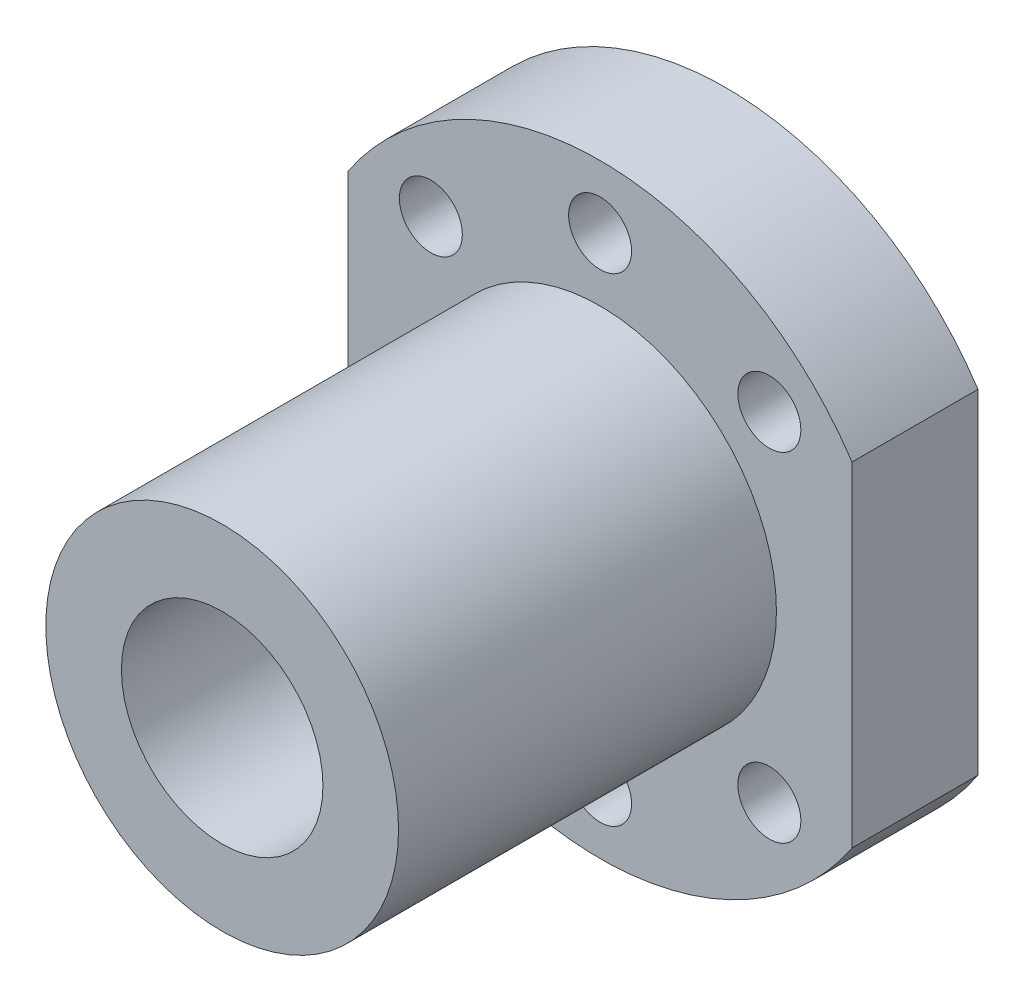
SolidWorks part; units mm, degrees
ref_plane "前视基准面" through (0, 0, 0) normal (0, 0, 1) x (1, 0, 0)
ref_plane "上视基准面" through (0, 0, 0) normal (0, 1, 0) x (1, 0, 0)
ref_plane "右视基准面" through (0, 0, 0) normal (1, 0, 0) x (0, 0, -1)
sketch "草图1" plane through (0, 0, 0) normal (0, 0, 1) x (1, 0, 0)
  line L0 (0, 24) -> (0, -24) construction
  line L1 (20, 13.2665) -> (20, -13.2665)
  line L2 (-20, -13.2665) -> (-20, 13.2665)
  line L3 (-20, 0) -> (20, 0) construction
  line L4 (0, 0) -> (-13.435, 13.435) construction
  line L5 (0, 0) -> (13.435, 13.435) construction
  line L6 (0, 0) -> (13.435, -13.435) construction
  arc A0 (-20, -13.2665) -> (20, -13.2665) centre (0, 0) ccw
  arc A1 (20, 13.2665) -> (-20, 13.2665) centre (0, 0) ccw
  circle A2 centre (0, 0) radius 19 construction
  circle A3 centre (0, 19) radius 2.5
  circle A4 centre (13.435, 13.435) radius 2.5
  circle A5 centre (-13.435, 13.435) radius 2.5
  circle A6 centre (0, -19) radius 2.5
  circle A7 centre (-13.435, -13.435) radius 2.5
  circle A8 centre (13.435, -13.435) radius 2.5
  circle A9 centre (0, 0) radius 8
  dimension "D1" = 48
  dimension "D4" = 5
  dimension "D5" = 5
  dimension "D6" = 5
  dimension "D7" = 38
  dimension "D10" = 16
  dimension "D2" = 20
  dimension "D3" = 20
  dimension "D8" = 45
  dimension "D9" = 45
extrude "凸台-拉伸1" add sketch "草图1" along normal blind 10
sketch "草图2" plane through (0, 0, 10) normal (0, 0, 1) x (1, 0, 0)
  circle A0 centre (0, 0) radius 14
  circle A1 centre (0, 0) radius 8
  dimension "D1" = 28
  dimension "D2" = 16
extrude "凸台-拉伸2" add sketch "草图2" along normal blind 30
